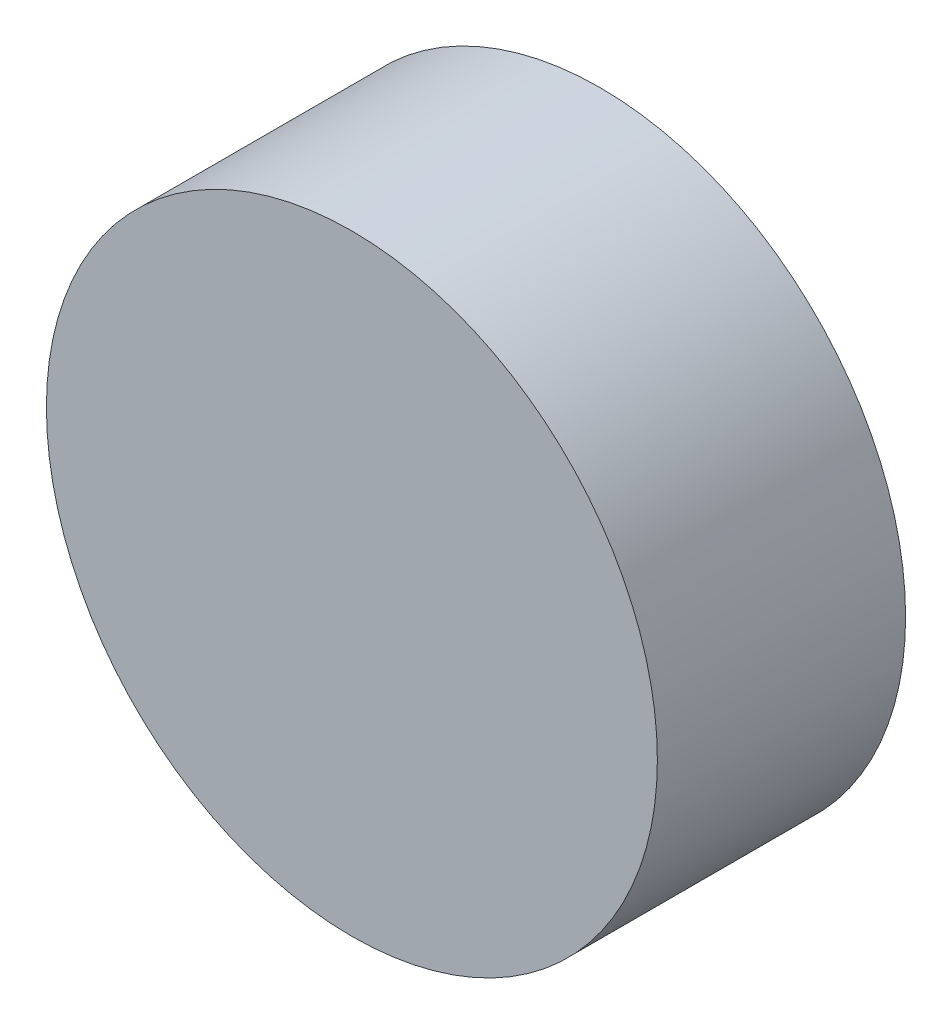
SolidWorks part; units mm, degrees
ref_plane "前视基准面" through (0, 0, 0) normal (0, 0, 1) x (1, 0, 0)
ref_plane "上视基准面" through (0, 0, 0) normal (0, 1, 0) x (1, 0, 0)
ref_plane "右视基准面" through (0, 0, 0) normal (1, 0, 0) x (0, 0, -1)
sketch "草图1" plane through (0, 0, 0) normal (0, 0, 1) x (1, 0, 0)
  circle A0 centre (-8.4121, 9.4135) radius 4
extrude "凸台-拉伸1" add sketch "草图1" along normal blind 3.25
